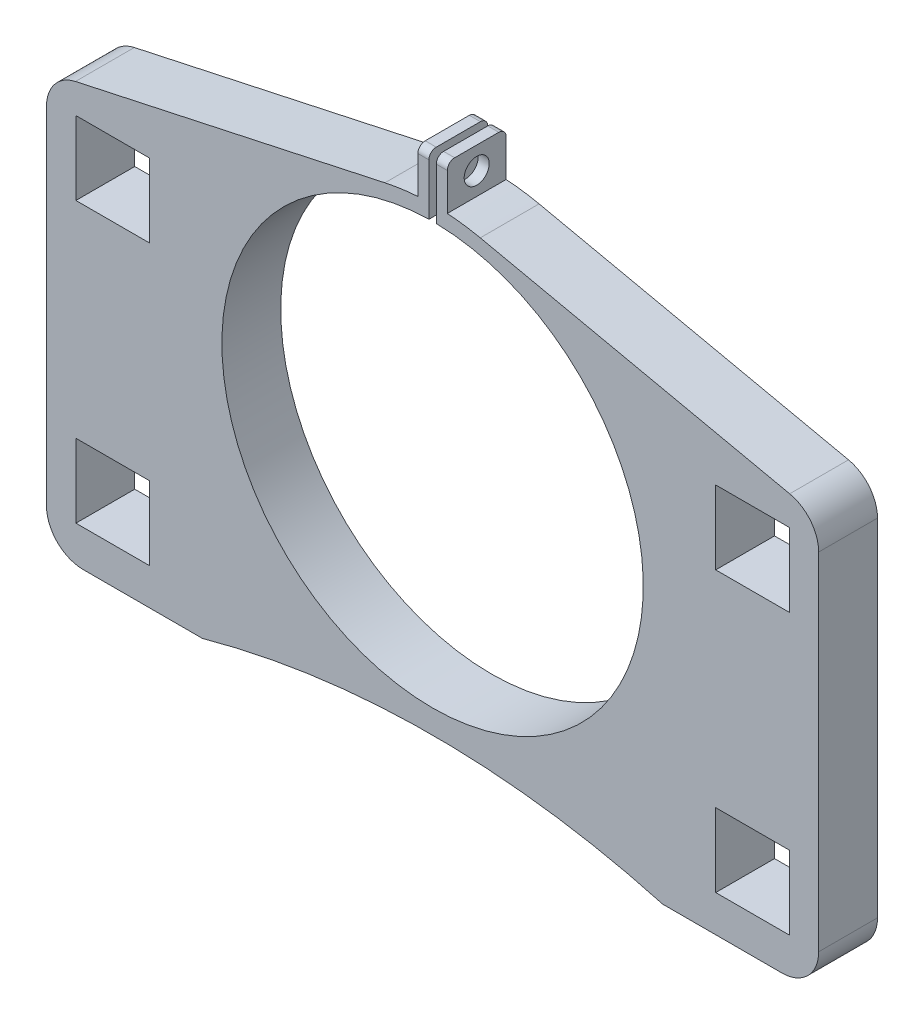
SolidWorks part; units mm, degrees
ref_plane "Ebene vorne" through (0, 0, 0) normal (0, 0, 1) x (1, 0, 0)
ref_plane "Ebene oben" through (0, 0, 0) normal (0, 1, 0) x (1, 0, 0)
ref_plane "Ebene rechts" through (0, 0, 0) normal (1, 0, 0) x (0, 0, -1)
sketch "Skizze1" plane through (0, 0, 0) normal (0, 0, 1) x (1, 0, 0)
  circle A0 centre (0, 0) radius 28.65
  circle A1 centre (0, 0) radius 30.65
  dimension "D1" = 57.3
  dimension "D2" = 2
extrude "Aufsatz-Linear austragen1" add sketch "Skizze1" along normal blind 8
sketch "Skizze2" plane through (0, 0, 8) normal (0, 0, 1) x (1, 0, 0)
  line L0 (0, 0) -> (28.5, 0) construction
  line L1 (0, 0) -> (0, 17.0738) construction
  line L3 (52.5, -36.1061) -> (52.5, 20)
  line L5 (-6.4605, 29.8591) -> (-6.4816, 29.9568)
  line L10 (6.4605, 29.8591) -> (6.4816, 29.9568)
  line L11 (52.5, 20) -> (6.4816, 29.9568)
  line L12 (-52.5, -36.1061) -> (-52.5, 20)
  line L14 (0, 0) -> (21.6021, -21.6021) construction
  line L16 (-31.2888, -36.1061) -> (-52.5, -36.1061)
  line L17 (31.2888, -36.1061) -> (52.5, -36.1061)
  line L27 (-52.5, 20) -> (-6.4816, 29.9568)
  circle A0 centre (0, 0) radius 30.65 construction
  arc A1 (31.2888, -36.1061) -> (-31.2888, -36.1061) centre (0, -148.8738) ccw
  arc A2 (-21.1031, -22.0898) -> (-6.4605, 29.8591) centre (0, 0) cw
  circle A3 centre (0, 0) radius 30.65 construction
  arc A4 (-21.1031, -22.0898) -> (6.4605, 29.8591) centre (0, 0) ccw
  dimension "D4" = 0.1
  dimension "D3" = 20
  dimension "D6" = 45
extrude "Aufsatz-Linear austragen2" add sketch "Skizze2" against normal up to surface (8 mm away) up to face at (30.65, 0, 0)
fillet "Verrundung1" [suppressed] radius 6
sketch "Skizze3" plane through (0, 0, 8) normal (0, 0, 1) x (1, 0, 0)
  line L0 (0, 0) -> (0, 35.0949) construction
  line L1 (-0.5, 30.7687) -> (0.5, 30.7687)
  line L2 (0.5, 30.7687) -> (0.5, 27.9134)
  line L3 (0.5, 27.9134) -> (-0.5, 27.9134)
  line L4 (-0.5, 30.7687) -> (-0.5, 27.9134)
  point P8 (0, 27.9134)
  point P9 (0, 30.7687)
  dimension "D1" = 1
extrude "Schnitt-Linear austragen1" cut sketch "Skizze3" against normal blind 10
sketch "Skizze4" plane through (0, 0, 8) normal (0, 0, 1) x (1, 0, 0)
  line L0 (0.5, 30.6459) -> (0.5, 36.6459)
  line L1 (0.5, 36.6459) -> (2, 36.6459)
  line L2 (2, 36.6459) -> (2, 29.0272)
  line L3 (2, 29.0272) -> (0.5, 30.6459)
  line L4 (0, 0) -> (0, 39.0521) construction
  line L5 (-2, 29.0272) -> (-0.5, 30.6459)
  line L6 (-2, 36.6459) -> (-2, 29.0272)
  line L7 (-0.5, 36.6459) -> (-2, 36.6459)
  line L8 (-0.5, 30.6459) -> (-0.5, 36.6459)
  dimension "D1" = 1.5
  dimension "D2" = 6
extrude "Aufsatz-Linear austragen3" add sketch "Skizze4" against normal blind 8
sketch "Skizze5" plane through (-2, 0, 0) normal (-1, 0, 0) x (0, 0, 1)
  line L0 (4, 36.6459) -> (4, 30.5847) construction
  line L1 (0, 36.6459) -> (8, 36.6459) construction
  line L2 (8, 30.5847) -> (0, 30.5847) construction
  line L3 (0, 33.6153) -> (8, 33.6153) construction
  line L4 (0, 36.6459) -> (0, 30.5847) construction
  line L5 (8, 36.6459) -> (8, 30.5847) construction
  circle A0 centre (4, 33.6153) radius 2.75 construction
  circle A1 centre (4, 33.6153) radius 1.7
  dimension "D1" = 5.5
  dimension "D2" = 3.4
extrude "Schnitt-Linear austragen2" cut sketch "Skizze5" against normal blind 8
fillet "Verrundung2" radius 1 4 edges at (-1.25, 36.6459, 8) (-1.25, 36.6459, 0) (1.25, 36.6459, 8) (1.25, 36.6459, 0)
sketch "Skizze7" plane through (0, 0, 0) normal (0, 0, -1) x (-1, 0, 0)
  line L0 (-52.5, 20) -> (-52.5, -36.1061) construction
  line L1 (-48.5, 6.8655) -> (-38.5, 6.8655)
  line L2 (-48.5, 6.8655) -> (-48.5, 16.8655)
  line L3 (-48.5, 16.8655) -> (-38.5, 16.8655)
  line L4 (-38.5, 6.8655) -> (-38.5, 16.8655)
  line L5 (-48.5, 6.8655) -> (-38.5, 16.8655) construction
  line L6 (-48.5, 16.8655) -> (-38.5, 6.8655) construction
  line L7 (-48.5, 16.8655) -> (-48.5, 20.8655) construction
  line L8 (-6.4816, 29.9568) -> (-52.5, 20) construction
  line L9 (-48.5, -31.1345) -> (-38.5, -31.1345)
  line L10 (-48.5, -31.1345) -> (-48.5, -21.1345)
  line L11 (-48.5, -21.1345) -> (-38.5, -21.1345)
  line L12 (-38.5, -31.1345) -> (-38.5, -21.1345)
  line L13 (-48.5, -31.1345) -> (-38.5, -21.1345) construction
  line L14 (-48.5, -21.1345) -> (-38.5, -31.1345) construction
  line L15 (0, 0) -> (0, -20.2139) construction
  line L16 (48.5, -21.1345) -> (38.5, -31.1345) construction
  line L17 (48.5, -31.1345) -> (38.5, -21.1345) construction
  line L18 (48.5, 16.8655) -> (38.5, 6.8655) construction
  line L19 (48.5, 6.8655) -> (38.5, 16.8655) construction
  line L20 (38.5, -31.1345) -> (38.5, -21.1345)
  line L21 (48.5, -21.1345) -> (38.5, -21.1345)
  line L22 (48.5, -31.1345) -> (48.5, -21.1345)
  line L23 (48.5, -31.1345) -> (38.5, -31.1345)
  line L24 (38.5, 6.8655) -> (38.5, 16.8655)
  line L25 (48.5, 16.8655) -> (38.5, 16.8655)
  line L26 (48.5, 6.8655) -> (48.5, 16.8655)
  line L27 (48.5, 6.8655) -> (38.5, 6.8655)
  line L28 (0, 0) -> (-80.5188, 0) construction
  point P0 (-43.5, 11.8655)
  point P5 (-43.5, -26.1345)
  point P26 (43.5, -26.1345)
  point P27 (43.5, 11.8655)
  dimension "D1" = 10
  dimension "D2" = 4
  dimension "D3" = 4
  dimension "D4" = 10
  dimension "D5" = 38
extrude "Schnitt-Linear austragen4" cut sketch "Skizze7" against normal blind 10
fillet "Verrundung3" radius 5 4 edges at (52.5, 20, 4) (-52.5, 20, 4) (-52.5, -36.1061, 4) (52.5, -36.1061, 4)
